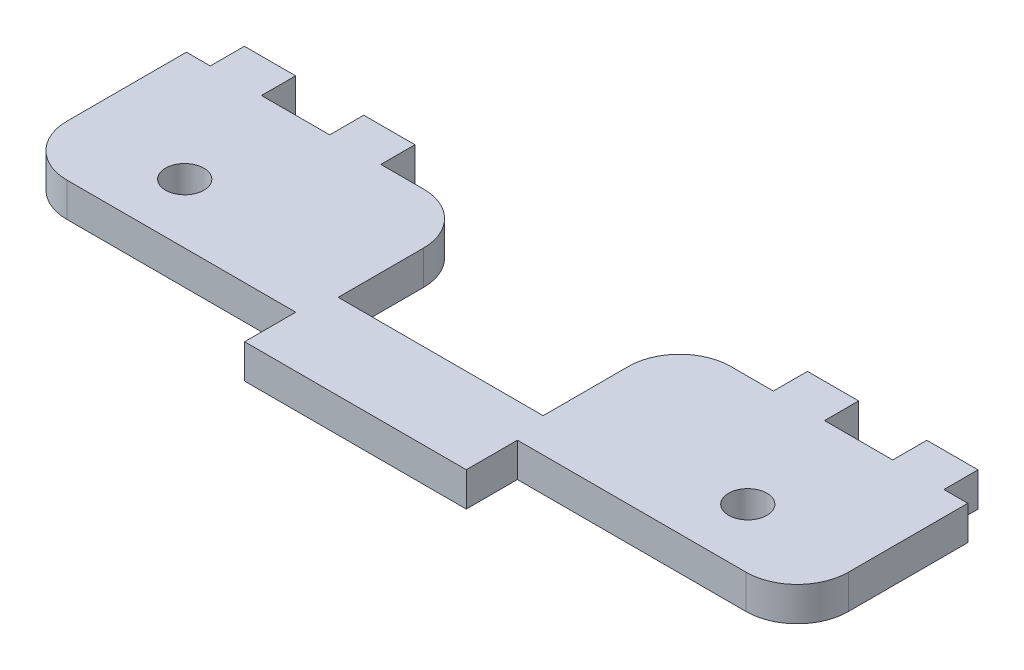
SolidWorks part; units mm, degrees
ref_plane "Front" through (0, 0, 0) normal (0, 0, 1) x (1, 0, 0)
ref_plane "Top" through (0, 0, 0) normal (0, 1, 0) x (1, 0, 0)
ref_plane "Right" through (0, 0, 0) normal (1, 0, 0) x (0, 0, -1)
sketch "Croquis1" plane through (0, 0, 0) normal (0, 1, 0) x (1, 0, 0)
  line L0 (-776.5744, 0) -> (38052.1471, 0) construction
  line L1 (0, -776.5744) -> (0, 38052.1471) construction
  line L2 (19.91, 0) -> (6.5, 0)
  line L3 (-22.91, 3) -> (-22.91, 10)
  line L4 (-22.91, 10) -> (-21.51, 10)
  line L5 (-14.51, 10) -> (-14.51, 12)
  line L6 (-14.51, 12) -> (-11.51, 12)
  line L7 (-11.51, 12) -> (-11.51, 10)
  line L8 (-11.51, 10) -> (-9.01, 10)
  line L9 (-6.01, 7) -> (-6.01, 2)
  line L10 (-6.01, 2) -> (6.01, 2)
  line L11 (6.01, 7) -> (6.01, 2)
  line L12 (11.51, 10) -> (9.01, 10)
  line L13 (11.51, 12) -> (11.51, 10)
  line L14 (14.51, 12) -> (11.51, 12)
  line L15 (14.51, 10) -> (14.51, 12)
  line L16 (22.91, 10) -> (21.51, 10)
  line L17 (22.91, 3) -> (22.91, 10)
  line L18 (-1000, 2) -> (49000, 2) construction
  line L19 (-6.5, 0) -> (-19.91, 0)
  line L20 (-13.01, -988) -> (-13.01, 49012) construction
  line L21 (-16.51, -988) -> (-16.51, 49012) construction
  line L22 (-18.51, 10) -> (-18.51, 12)
  line L23 (-18.51, 12) -> (-21.51, 12)
  line L24 (-21.51, 12) -> (-21.51, 10)
  line L25 (-18.51, 10) -> (-14.51, 10)
  line L26 (18.51, 10) -> (18.51, 12)
  line L27 (18.51, 12) -> (21.51, 12)
  line L28 (21.51, 12) -> (21.51, 10)
  line L29 (18.51, 10) -> (14.51, 10)
  line L30 (-6.5, -3) -> (6.5, -3)
  line L31 (-6.5, -3) -> (-6.5, 0)
  line L32 (6.5, -3) -> (6.5, 0)
  line L33 (-1009.01, 10) -> (48990.99, 10) construction
  circle A0 centre (-16.51, 3.5) radius 1.125
  arc A1 (-19.91, 0) -> (-22.91, 3) centre (-19.91, 3) cw
  circle A2 centre (16.51, 3.5) radius 1.125
  arc A3 (19.91, 0) -> (22.91, 3) centre (19.91, 3) ccw
  arc A4 (6.01, 7) -> (9.01, 10) centre (9.01, 7) cw
  arc A5 (-6.01, 7) -> (-9.01, 10) centre (-9.01, 7) ccw
  point P16 (0, 4)
  point P23 (0, 0)
  point P25 (-22.91, 10)
  point P28 (-22.91, 0)
  point P30 (-13.01, 12)
  point P31 (22.91, 10)
  point P34 (22.91, 0)
  point P37 (6.01, 10)
  point P40 (-6.01, 10)
  point P47 (0, -5)
  point P52 (6.125, -5)
  point P58 (22.0313, 0.8787)
  point P66 (0, 1)
  point P69 (0, -3)
  dimension "D10" = 3
  dimension "D11" = 3.5
  dimension "D12" = 3
  dimension "D13" = 3
  dimension "D15" = 6.4
  dimension "D16" = 6.5
  dimension "D17" = 13
  dimension "D14" = 2.25
  dimension "D21" = 3
  dimension "D4" = 8
  dimension "D18" = 3
  dimension "D1" = 22.91
  dimension "D2" = 10
  dimension "D3" = 8.4
  dimension "D5" = 2
  dimension "D6" = 3
  dimension "D8" = 5.5
extrude "Saliente-Extruir1" add sketch "Croquis1" along normal blind 2
sketch "Croquis2" plane through (0, 2, 0) normal (0, 1, 0) x (1, 0, 0)
  line L0 (0, -1000) -> (0, 49000) construction
  line L1 (14.51, 10) -> (11.51, 10)
  line L2 (-14.51, 12) -> (-11.51, 12)
  line L3 (-14.51, 12) -> (-14.51, 10)
  line L4 (-14.51, 10) -> (-11.51, 10)
  line L5 (-11.51, 12) -> (-11.51, 10)
  line L6 (11.51, 12) -> (11.51, 10)
  line L7 (14.51, 12) -> (11.51, 12)
  line L8 (14.51, 12) -> (14.51, 10)
  line L9 (-13.01, -988) -> (-13.01, 49012) construction
  line L10 (-16.51, -988) -> (-16.51, 49012) construction
  line L11 (-21.51, 12) -> (-21.51, 10)
  line L12 (-18.51, 12) -> (-21.51, 12)
  line L13 (-18.51, 12) -> (-18.51, 10)
  line L14 (-18.51, 10) -> (-21.51, 10)
  line L15 (21.51, 12) -> (21.51, 10)
  line L16 (18.51, 10) -> (21.51, 10)
  line L17 (18.51, 12) -> (18.51, 10)
  line L18 (18.51, 12) -> (21.51, 12)
  point P18 (-13.01, 12)
  dimension "D1" = 3.5
extrude "Cortar-Extruir1" [suppressed] cut sketch "Croquis2" against normal blind 1
sketch "Croquis3" plane through (0, 0, 0) normal (0, -1, 0) x (1, 0, 0)
  line L0 (0, -1000) -> (0, 49000) construction
  line L1 (-1000, 0) -> (49000, 0) construction
  line L2 (-1000, -5.5) -> (49000, -5.5) construction
  line L3 (-22.91, -10) -> (-22.91, -3) construction
  line L4 (-20.01, -5.5) -> (-13.01, -5.5)
  line L5 (-20.01, -5.5) -> (-20.01, -8)
  line L6 (-20.01, -8) -> (-13.01, -8)
  line L7 (-13.01, -5.5) -> (-13.01, -8)
  line L8 (-20.01, -1012) -> (-20.01, 48988) construction
  line L9 (-18.51, -12) -> (-21.51, -12) construction
  line L10 (-13.01, -1012) -> (-13.01, 48988) construction
  line L11 (-11.51, -12) -> (-14.51, -12) construction
  line L14 (20.01, -8) -> (13.01, -8)
  line L15 (13.01, -5.5) -> (13.01, -8)
  line L16 (20.01, -5.5) -> (13.01, -5.5)
  line L17 (20.01, -5.5) -> (20.01, -8)
  point P18 (-20.01, -12)
  point P23 (-13.01, -12)
  dimension "D2" = 7
  dimension "D3" = 2.5
  dimension "D4" = 2.9
  dimension "D1" = 5.5
extrude "Saliente-Extruir2" add sketch "Croquis3" along normal blind 2
